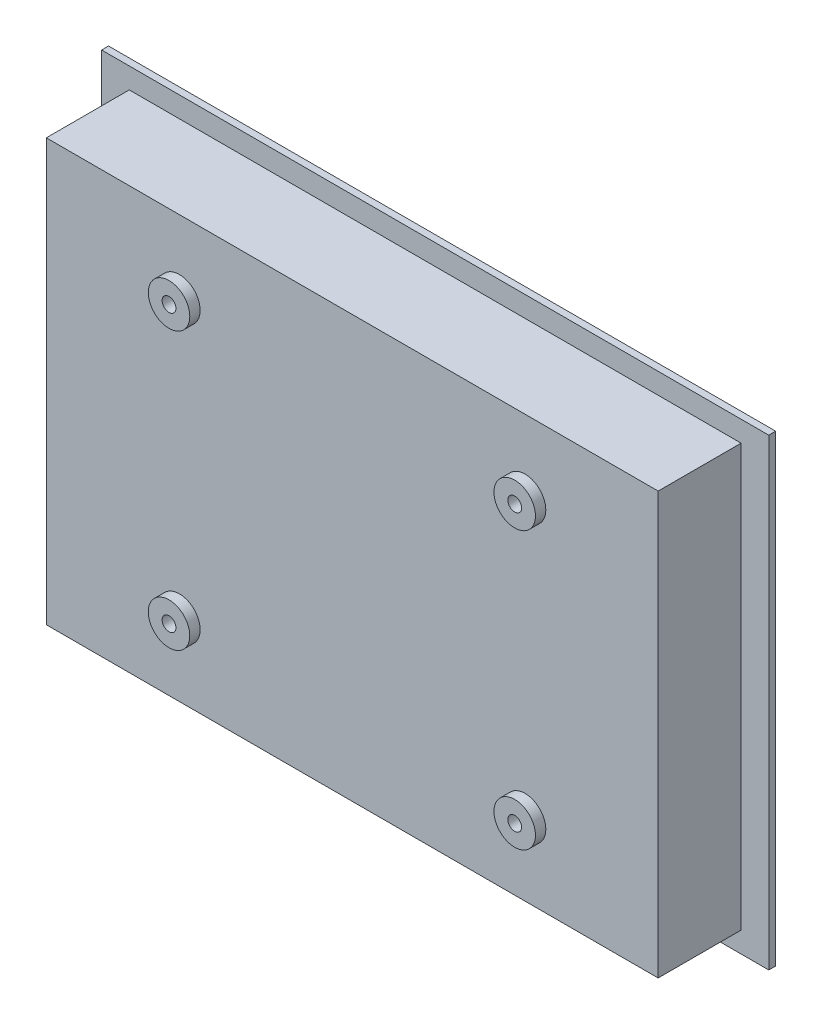
SolidWorks part; units mm, degrees
ref_plane "前视基准面" through (0, 0, 0) normal (0, 0, 1) x (1, 0, 0)
ref_plane "上视基准面" through (0, 0, 0) normal (0, 1, 0) x (1, 0, 0)
ref_plane "右视基准面" through (0, 0, 0) normal (1, 0, 0) x (0, 0, -1)
sketch "草图1" plane through (0, 0, 0) normal (0, 0, 1) x (1, 0, 0)
  line L1 (-96.5, 67) -> (96.5, 67)
  line L2 (-96.5, 67) -> (-96.5, -67)
  line L3 (-96.5, -67) -> (96.5, -67)
  line L4 (96.5, 67) -> (96.5, -67)
  line L5 (-96.5, 67) -> (96.5, -67) construction
  line L6 (-96.5, -67) -> (96.5, 67) construction
  point P0 (0, 0)
  dimension "D1" = 134
  dimension "D2" = 193
extrude "凸台-拉伸1" add sketch "草图1" along normal blind 2
sketch "草图2" plane through (0, 0, 2) normal (0, 0, 1) x (1, 0, 0)
  line L1 (-88.5, 61) -> (88.5, 61)
  line L2 (-88.5, 61) -> (-88.5, -61)
  line L3 (-88.5, -61) -> (88.5, -61)
  line L4 (88.5, 61) -> (88.5, -61)
  line L5 (-88.5, 61) -> (88.5, -61) construction
  line L6 (-88.5, -61) -> (88.5, 61) construction
  point P0 (0, 0)
  dimension "D1" = 177
  dimension "D2" = 122
extrude "凸台-拉伸2" add sketch "草图2" along normal blind 24
sketch "草图3" plane through (0, 0, 26) normal (0, 0, 1) x (1, 0, 0)
  line L1 (-50, 40) -> (50, 40) construction
  line L2 (-50, 40) -> (-50, -40) construction
  line L3 (-50, -40) -> (50, -40) construction
  line L4 (50, 40) -> (50, -40) construction
  line L5 (-50, 40) -> (50, -40) construction
  line L6 (-50, -40) -> (50, 40) construction
  circle A0 centre (-50, 40) radius 2
  circle A1 centre (-50, -40) radius 2
  circle A2 centre (50, -40) radius 2
  circle A3 centre (50, 40) radius 2
  point P0 (0, 0)
  dimension "D3" = 4
  dimension "D4" = 4
  dimension "D5" = 4
  dimension "D6" = 4
  dimension "D1" = 100
  dimension "D2" = 80
extrude "切除-拉伸1" cut sketch "草图3" against normal blind 5 and the other way blind 10
sketch "草图4" plane through (0, 0, 26) normal (0, 0, 1) x (1, 0, 0)
  circle A0 centre (-50, 40) radius 6
  circle A1 centre (-50, -40) radius 6
  circle A2 centre (50, -40) radius 6
  circle A3 centre (50, 40) radius 6
  circle A4 centre (50, 40) radius 2
  circle A5 centre (50, -40) radius 2
  circle A6 centre (-50, -40) radius 2
  circle A7 centre (-50, 40) radius 2
  dimension "D1" = 12
  dimension "D2" = 12
  dimension "D3" = 4
  dimension "D4" = 12
  dimension "D5" = 4
  dimension "D6" = 12
  dimension "D7" = 4
  dimension "D8" = 4
extrude "凸台-拉伸3" add sketch "草图4" along normal blind 3
